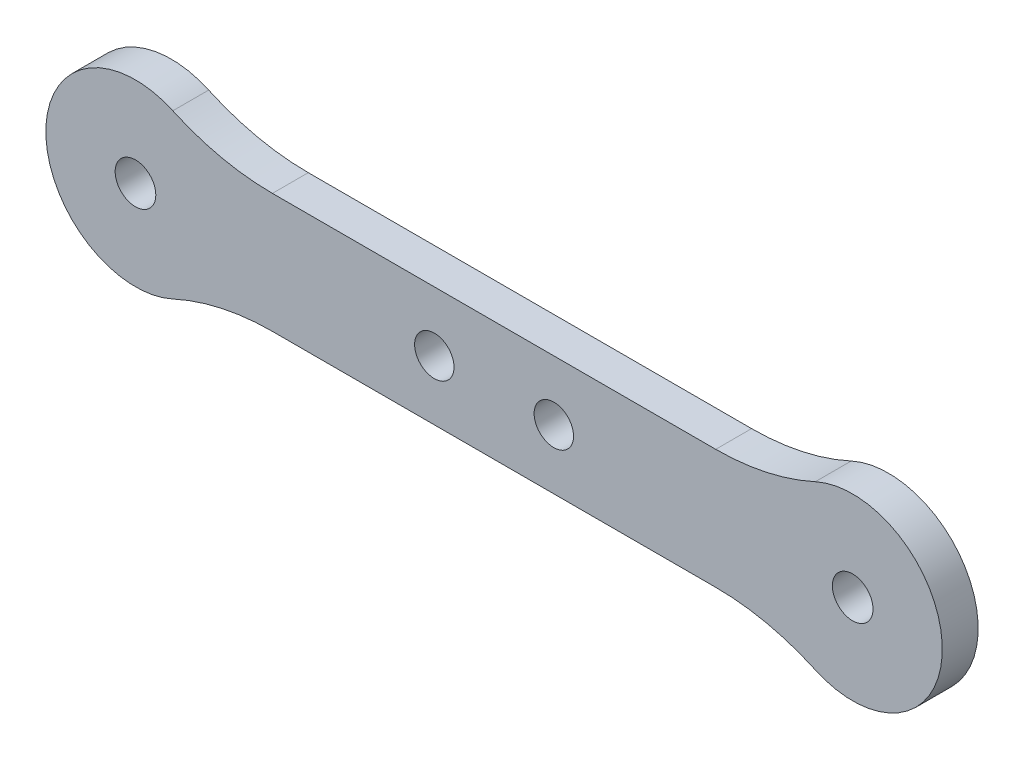
SolidWorks part; units mm, degrees
ref_plane "Plano frontal" through (0, 0, 0) normal (0, 0, 1) x (1, 0, 0)
ref_plane "Plano superior" through (0, 0, 0) normal (0, 1, 0) x (1, 0, 0)
ref_plane "Plano direito" through (0, 0, 0) normal (1, 0, 0) x (0, 0, -1)
sketch "Esboço1" plane through (0, 0, 0) normal (0, 0, 1) x (1, 0, 0)
  line L0 (5.5902, -5) -> (54.4098, -5)
  line L1 (0, 0) -> (60, 0) construction
  line L2 (5.5902, 5) -> (54.4098, 5)
  line L3 (0, 5) -> (80, 5) construction
  line L4 (0, -5) -> (80, -5) construction
  line L5 (30, 5) -> (30, -5) construction
  line L7 (0, 0) -> (80, 0) construction
  circle A0 centre (0, 0) radius 1.7
  circle A1 centre (25, 0) radius 1.65
  circle A2 centre (0, 0) radius 1.7
  arc A3 (5.5902, 5) -> (5.5902, -5) centre (0, 0) ccw
  circle A4 centre (35, 0) radius 1.65
  circle A5 centre (0, 0) radius 1.7
  circle A8 centre (0, 0) radius 1.7
  circle A9 centre (60, 0) radius 1.7
  circle A11 centre (0, 0) radius 1.7
  circle A13 centre (0, 0) radius 1.7
  circle A16 centre (60, 0) radius 1.7
  circle A18 centre (60, 0) radius 1.7
  circle A20 centre (60, 0) radius 1.7
  arc A22 (54.4098, 5) -> (54.4098, -5) centre (60, 0) cw
  circle A23 centre (60, 0) radius 1.7
  circle A25 centre (60, 0) radius 1.7
  point P14 (30, 0)
  point P32 (0, 0)
  dimension "D1" = 3.4
  dimension "D3" = 3.3
  dimension "D6" = 6
  dimension "D8" = 15
  dimension "D2" = 5
  dimension "D5" = 5
  dimension "D7" = 30
  dimension "D9" = 10
extrude "Ressalto-extrusão1" add sketch "Esboço1" along normal blind 3
fillet "Filete1" radius 20 4 edges at (5.5902, -5, 1.5) (54.4098, -5, 1.5) (54.4098, 5, 1.5) (5.5902, 5, 1.5)
